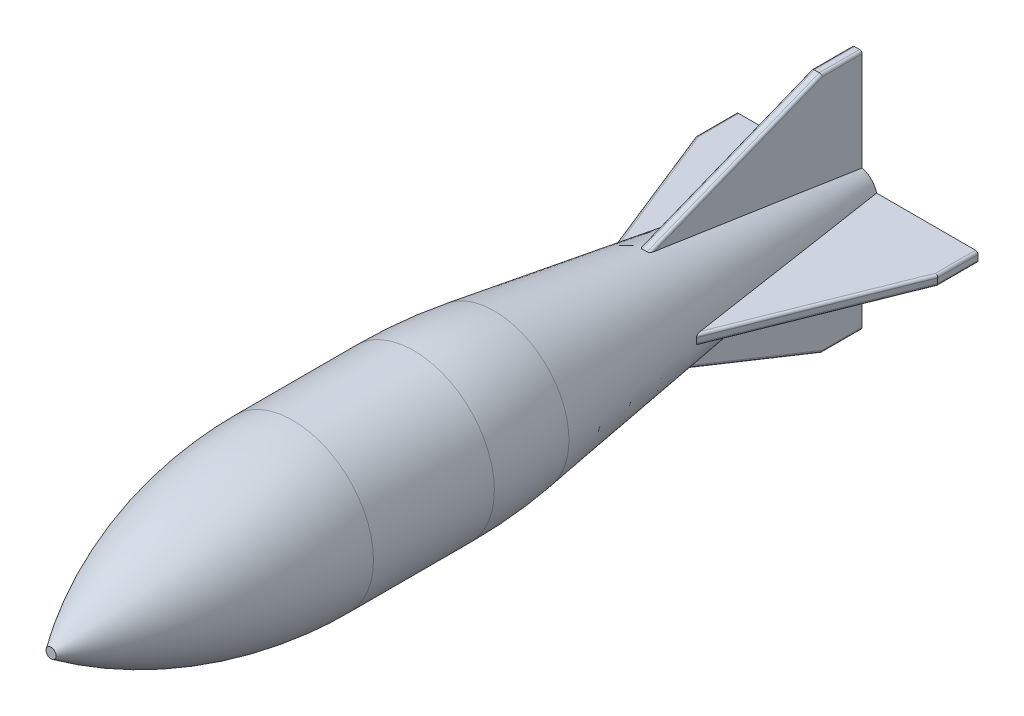
SolidWorks part; units mm, degrees
ref_plane "Front Plane" through (0, 0, 0) normal (0, 0, 1) x (1, 0, 0)
ref_plane "Top Plane" through (0, 0, 0) normal (0, 1, 0) x (1, 0, 0)
ref_plane "Right Plane" through (0, 0, 0) normal (1, 0, 0) x (0, 0, -1)
sketch "Sketch3" plane through (0, 0, 0) normal (1, 0, 0) x (0, 0, -1)
  line L0 (0, 0) -> (127, 0)
  line L1 (127, 0) -> (127, 3.175)
  line L2 (12.8948, 0) -> (95.4448, 0)
  line L3 (38.1, 12.7) -> (57.15, 12.7)
  line L5 (69.85, 11.7523) -> (127, 3.175)
  line L6 (0, 0) -> (0, 0.7937)
  line L7 (95.4448, 0) -> (95.4448, 3.9688)
  line L8 (95.4448, 3.9688) -> (91.476, 3.9687)
  line L9 (22.4198, 9.525) -> (79.0564, 9.525)
  line L10 (95.4448, 3.9688) -> (95.4448, 7.9109)
  arc A1 (57.15, 12.7) -> (69.85, 11.7523) centre (57.15, -72.8672) cw
  arc A2 (0, 0.7937) -> (38.1, 12.7) centre (38.1, -54.2131) cw
  circle A3 centre (22.4198, 0) radius 9.525
  arc A4 (79.0564, 9.525) -> (85.9805, 6.4273) centre (79.0564, 0.2377) cw
  arc A5 (85.9805, 6.4273) -> (91.476, 3.9687) centre (91.476, 11.3399) ccw
  dimension "D1" = 12.7
  dimension "D5" = 57.15
  dimension "D6" = 0.7937
  dimension "D8" = 82.55
  dimension "D9" = 19.05
  dimension "D2" = 38.1
  dimension "D3" = 3.175
  dimension "D4" = 19.05
  dimension "D7" = 127
  dimension "D10" = 3.9688
  dimension "D11" = 3.9688
revolve "Revolve2" add sketch "Sketch3" angle 360 about L0
sketch "Sketch5" plane through (0, 0, 0) normal (1, 0, 0) x (0, 0, -1)
  line L1 (120.65, 19.05) -> (127, 19.05)
  line L2 (120.65, 19.05) -> (88.9, 6.35)
  line L3 (127, 19.05) -> (127, 0)
  line L6 (88.9, 6.35) -> (127, 0)
  line L7 (127, -3.175) -> (127, 3.175) construction
  dimension "D1" = 19.05
  dimension "D2" = 6.35
  dimension "D3" = 6.35
  dimension "D4" = 38.1
extrude "Boss-Extrude2" add sketch "Sketch5" along normal mid plane 1.5875
fillet "Fillet2" radius 0.3969 4 edges at (-0.7937, 19.05, -123.825) (0.7937, 19.05, -123.825) (-0.7937, 13.6107, -107.0517) (0.7937, 13.6107, -107.0517)
ref_plane "Plane1" through (0, 0, -114.3) normal (0, 0, -1) x (-1, 0, 0)
sketch "Sketch6" plane through (0, 0, -114.3) normal (0, 0, -1) x (-1, 0, 0)
  circle A0 centre (0, 0) radius 6.35
  dimension "D1" = 12.7
pattern_circular "CirPattern5" count 4 over 360 about axis through (0, 0, 0) along (0, 0, 1) of "Fillet2", "Boss-Extrude2"
